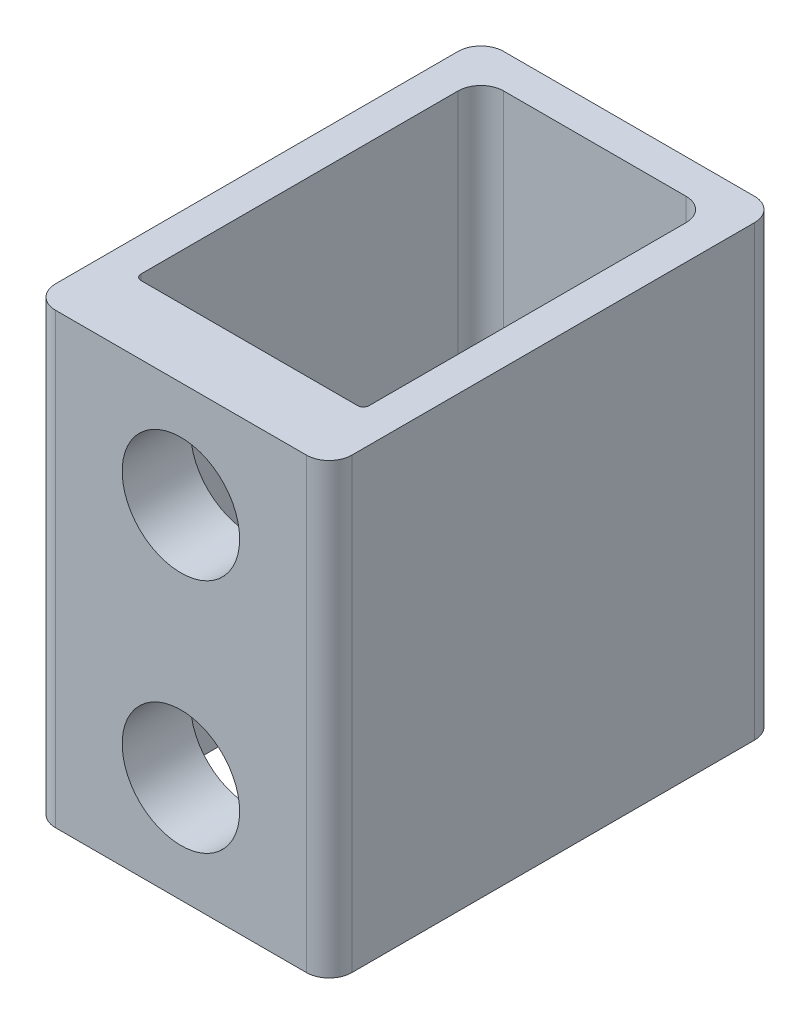
SolidWorks part; units mm, degrees
ref_plane "Alzado" through (0, 0, 0) normal (0, 0, 1) x (1, 0, 0)
ref_plane "Planta" through (0, 0, 0) normal (0, 1, 0) x (1, 0, 0)
ref_plane "Vista lateral" through (0, 0, 0) normal (1, 0, 0) x (0, 0, -1)
sketch "Croquis1" plane through (0, 0, 0) normal (0, 1, 0) x (1, 0, 0)
  line L0 (-4.75, -6.825) -> (4.75, -6.825)
  line L1 (-5.5, 9.825) -> (5.5, 9.825)
  line L2 (-6.5, 8.825) -> (-6.5, -8.825)
  line L3 (-5.5, -9.825) -> (5.5, -9.825)
  line L4 (6.5, 8.825) -> (6.5, -8.825)
  line L5 (-6.5, 9.825) -> (4.5153, -6.825) construction
  line L6 (-6.5, -9.825) -> (-6.2647, -9.4694) construction
  line L7 (-4, 8.325) -> (4, 8.325)
  line L8 (-5, 7.325) -> (-5, -6.575)
  line L10 (5, 7.325) -> (5, -6.575)
  line L11 (-5, 8.325) -> (4.0991, -6.825) construction
  line L12 (-5, -8.325) -> (5, 8.325) construction
  line L13 (-4.5153, -6.825) -> (6.5, 9.825) construction
  line L15 (6.2647, -9.4694) -> (6.5, -9.825) construction
  arc A0 (5.5, 9.825) -> (6.5, 8.825) centre (5.5, 8.825) cw
  arc A1 (5.5, -9.825) -> (6.5, -8.825) centre (5.5, -8.825) ccw
  arc A2 (-6.5, -8.825) -> (-5.5, -9.825) centre (-5.5, -8.825) ccw
  arc A3 (-5.5, 9.825) -> (-6.5, 8.825) centre (-5.5, 8.825) ccw
  arc A4 (4, 8.325) -> (5, 7.325) centre (4, 7.325) cw
  arc A7 (-4, 8.325) -> (-5, 7.325) centre (-4, 7.325) ccw
  arc A8 (4.75, -6.825) -> (5, -6.575) centre (4.75, -6.575) ccw
  arc A9 (-4.75, -6.825) -> (-5, -6.575) centre (-4.75, -6.575) cw
  point P0 (0, 0)
  point P18 (0, 0)
  dimension "D3" = 1
  dimension "D4" = 1
  dimension "D6" = 0.25
  dimension "D1" = 13
  dimension "D2" = 19.65
  dimension "D5" = 1.5
extrude "Saliente-Extruir1" add sketch "Croquis1" against normal blind 19.65
sketch "Croquis2" plane through (0, 0, 9.825) normal (0, 0, 1) x (1, 0, 0)
  line L0 (-5.5, 0) -> (5.5, 0) construction
  line L1 (-5.5, -19.65) -> (5.5, -19.65) construction
  circle A0 centre (0, -4.65) radius 2.575
  circle A1 centre (0, -15) radius 2.575
  point P9 (0, 0)
  point P10 (0, -19.65)
  dimension "D1" = 5.15
  dimension "D2" = 4.65
  dimension "D3" = 4.65
extrude "Cortar-Extruir1" cut sketch "Croquis2" against normal blind 8.65
